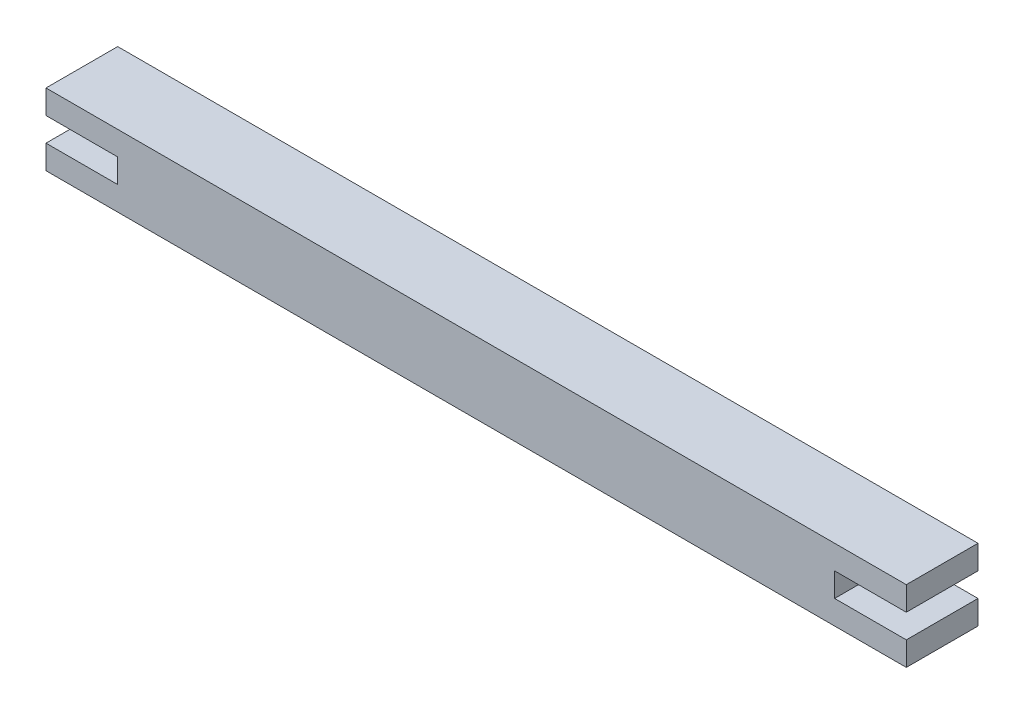
SolidWorks part; units mm, degrees
ref_plane "Alzado" through (0, 0, 0) normal (0, 0, 1) x (1, 0, 0)
ref_plane "Planta" through (0, 0, 0) normal (0, 1, 0) x (1, 0, 0)
ref_plane "Vista lateral" through (0, 0, 0) normal (1, 0, 0) x (0, 0, -1)
sketch "Croquis1" plane through (0, 0, 0) normal (0, 1, 0) x (1, 0, 0)
  line L0 (-150, 215) -> (150, 215) construction
  line L1 (-150, -200) -> (150, -200) construction
  line L2 (-150, -200) -> (-150, 200) construction
  line L3 (-150, 200) -> (150, 200) construction
  line L4 (150, -200) -> (150, 200) construction
  line L5 (-150, -200) -> (150, 200) construction
  line L6 (-150, 200) -> (150, -200) construction
  line L8 (-150, 200) -> (150, 200)
  line L9 (-150, 200) -> (-150, 230)
  line L10 (-150, 230) -> (150, 230)
  line L11 (150, 200) -> (150, 230)
  line L12 (-150, 200) -> (150, 230) construction
  line L13 (-150, 230) -> (150, 200) construction
  point P0 (0, 0)
  point P8 (0, 215)
  dimension "D1" = 300
  dimension "D2" = 400
  dimension "D3" = 15
  dimension "D4" = 30
extrude "Saliente-Extruir1" add sketch "Croquis1" along normal mid plane 30
sketch "Croquis2" plane through (0, 0, 0) normal (0, 1, 0) x (1, 0, 0)
  line L0 (150, 200) -> (150, 230) construction
  line L1 (-180, 200) -> (180, 200)
  line L2 (-180, 200) -> (-180, 230)
  line L3 (-180, 230) -> (180, 230)
  line L4 (180, 200) -> (180, 230)
  line L5 (-180, 200) -> (180, 230) construction
  line L6 (-180, 230) -> (180, 200) construction
  line L7 (-150, 230) -> (-150, 200) construction
  point P0 (0, 215)
  dimension "D1" = 30
  dimension "D2" = 30
extrude "Saliente-Extruir2" add sketch "Croquis2" along normal mid plane 10 from offset 10
mirror "Simetría1" about plane through (0, 0, 0) normal (0, 1, 0) of "Saliente-Extruir2"
